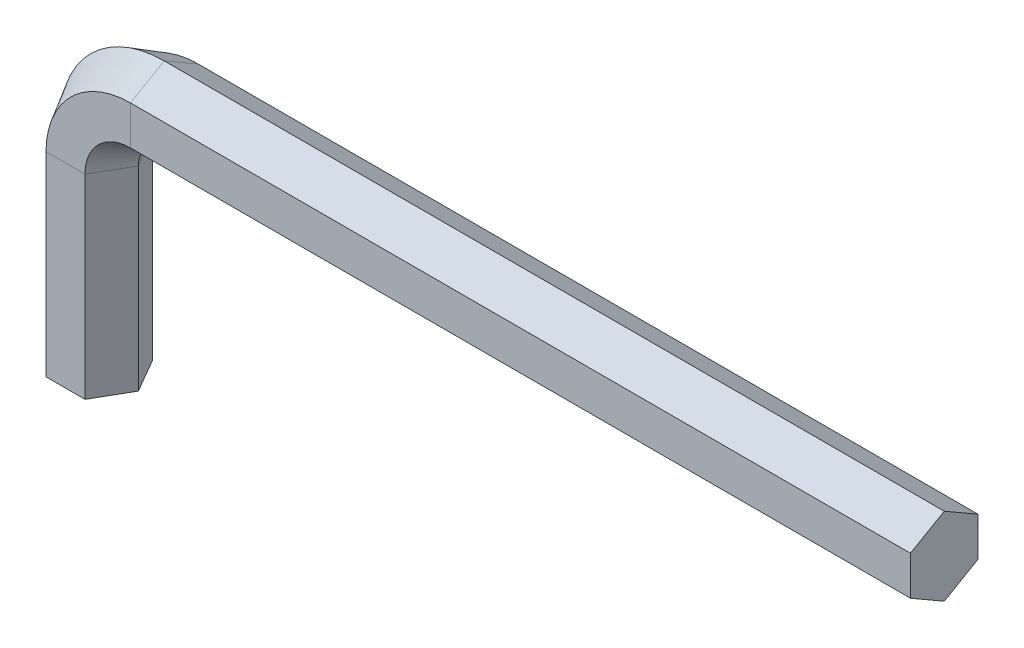
SolidWorks part; units mm, degrees
ref_plane "Front Plane" through (0, 0, 0) normal (0, 0, 1) x (1, 0, 0)
ref_plane "Top Plane" through (0, 0, 0) normal (0, 1, 0) x (1, 0, 0)
ref_plane "Right Plane" through (0, 0, 0) normal (1, 0, 0) x (0, 0, -1)
sketch "Sketch1" plane through (0, 0, 0) normal (0, 0, 1) x (1, 0, 0)
  line L0 (0, 0) -> (0, 15)
  line L1 (5, 20) -> (65, 20)
  arc A0 (5, 20) -> (0, 15) centre (5, 15) ccw
  point P6 (0, 20)
  dimension "D3" = 5
  dimension "D1" = 65
  dimension "D2" = 20
sketch "Sketch2" plane through (0, 0, 0) normal (0, 1, 0) x (1, 0, 0)
  line L0 (0, 0) -> (5, 0) construction
  line L1 (1.5, -2.5981) -> (3, 0)
  line L2 (3, 0) -> (1.5, 2.5981)
  line L3 (1.5, 2.5981) -> (-1.5, 2.5981)
  line L4 (-1.5, 2.5981) -> (-3, 0)
  line L5 (-3, 0) -> (-1.5, -2.5981)
  line L6 (-1.5, -2.5981) -> (1.5, -2.5981)
  circle A0 centre (0, 0) radius 2.5981 construction
  point P1 (0, 0)
  dimension "D1" = 3
sweep "Sweep1" add profiles "Sketch2" path "Sketch1"
